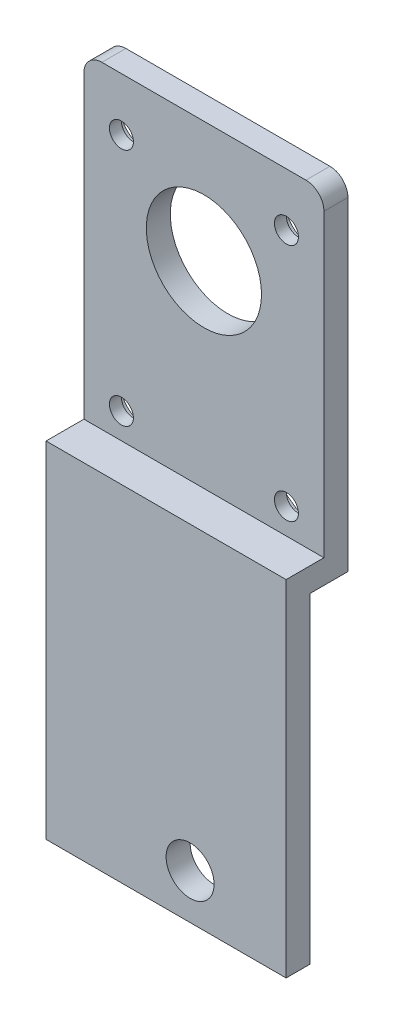
SolidWorks part; units mm, degrees
ref_plane "Front Plane" through (0, 0, 0) normal (0, 0, 1) x (1, 0, 0)
ref_plane "Top Plane" through (0, 0, 0) normal (0, 1, 0) x (1, 0, 0)
ref_plane "Right Plane" through (0, 0, 0) normal (1, 0, 0) x (0, 0, -1)
sketch "Sketch1" plane through (0, 0, 0) normal (0, 0, 1) x (1, 0, 0)
  line L0 (13.75, -19.7) -> (9.6769, -16.8) construction
  line L8 (20, -29) -> (-20, -29)
  line L9 (20, -29) -> (20, 26)
  line L11 (17, 29) -> (-17, 29)
  line L14 (-20, -29) -> (-20, 26)
  line L15 (20, -29) -> (-20, 29) construction
  line L16 (20, 29) -> (-20, -29) construction
  line L17 (11.314, -23.1214) -> (7.2409, -20.2214)
  line L18 (16.186, -16.2786) -> (12.1129, -13.3786)
  line L19 (0, -29) -> (0, 29) construction
  circle A18 centre (-13.75, 20.15) radius 4.2
  circle A19 centre (13.75, 20.15) radius 4.2
  circle A20 centre (-13.75, -19.7) radius 4.2
  arc A21 (11.314, -23.1214) -> (16.186, -16.2786) centre (13.75, -19.7) ccw
  arc A22 (12.1129, -13.3786) -> (7.2409, -20.2214) centre (9.6769, -16.8) ccw
  circle A23 centre (0, 8.8) radius 9.6
  circle A24 centre (-5.725, -6.1) radius 4.2
  circle A25 centre (5.725, -6.1) radius 4.2
  arc A26 (20, 26) -> (17, 29) centre (17, 26) ccw
  arc A27 (-20, 26) -> (-17, 29) centre (-17, 26) cw
  point P0 (0, 0)
  point P9 (0, 0)
  point P10 (19.6497, -28.492)
  point P12 (0, 0)
  point P13 (0, 0)
  point P14 (6.2555, -14.364)
  point P15 (0, 0)
  point P19 (0, 0)
  point P21 (0, 0)
  point P22 (0, 0)
  point P31 (11.7135, -18.25)
  point P37 (5.725, -10.3)
  point P38 (0, 0)
  point P39 (0, 0)
  point P43 (20, 29)
  point P46 (-20, 29)
  point P47 (1.9002, -20.2214)
  point P48 (-25.7648, -19.7)
  point P49 (-5.725, -14.8966)
  point P50 (7.0698, -20.2214)
  point P51 (-36.8241, -19.7)
  point P52 (11.0425, -18.4247)
  point P54 (0, 0)
  point P55 (0, 0)
  dimension "D1" = 58
  dimension "D2" = 40
  dimension "D3" = 3
  dimension "D4" = 8.4
  dimension "D5" = 8.4
  dimension "D6" = 19.2
  dimension "D7" = 9.3
  dimension "D8" = 27.5
  dimension "D9" = 12.2
  dimension "D10" = 5
  dimension "D11" = 39.85
  dimension "D12" = 20.2
  dimension "D13" = 11.45
  dimension "D14" = 22.9
extrude "Boss-Extrude1" add sketch "Sketch1" along normal blind 2
sketch "Sketch2" plane through (0, -29, 0) normal (0, -1, 0) x (1, 0, 0)
  line L1 (-20, 2) -> (20, 2)
  line L2 (-20, 2) -> (-20, 0)
  line L3 (-20, 0) -> (20, 0)
  line L4 (20, 2) -> (20, 0)
  point P6 (20, 2)
  point P8 (-20, 0)
extrude "Cut-Extrude1" cut sketch "Sketch2" against normal blind 1
sketch "Sketch4" plane through (0, 0, 2) normal (0, 0, 1) x (1, 0, 0)
  line L0 (20, -28) -> (20, 26) construction
  line L1 (-17, 29) -> (17, 29)
  line L2 (-20, 26) -> (-20, -28)
  line L3 (-20, -28) -> (20, -28)
  line L4 (20, 26) -> (20, -28)
  line L5 (-20, -28) -> (-20, 26) construction
  line L6 (20, -28) -> (-20, -28) construction
  line L7 (17, 29) -> (-17, 29) construction
  circle A2 centre (-13.75, -19.7) radius 2
  circle A3 centre (-13.75, 20.15) radius 2
  circle A4 centre (13.75, 20.15) radius 2
  arc A8 (17, 29) -> (20, 26) centre (17, 26) cw
  arc A9 (-17, 29) -> (-20, 26) centre (-17, 26) ccw
  circle A10 centre (13.75, -19.7) radius 2
  circle A11 centre (0, 8.8) radius 9.6
  circle A12 centre (0, 8.8) radius 9.6 construction
  dimension "D1" = 4
  dimension "D2" = 3
extrude "Boss-Extrude3" add sketch "Sketch4" along normal blind 2
sketch "Sketch5" plane through (0, 0, 4) normal (0, 0, 1) x (1, 0, 0)
  line L0 (-20, 26) -> (-20, -28) construction
  line L1 (-20, -24) -> (20, -24)
  line L2 (-20, -24) -> (-20, -28)
  line L3 (-20, -28) -> (20, -28)
  line L4 (20, -24) -> (20, -28)
  line L5 (20, -28) -> (20, 26) construction
  dimension "D1" = 4
extrude "Boss-Extrude4" add sketch "Sketch5" along normal blind 2.3
sketch "Sketch7" plane through (0, 0, 6.3) normal (0, 0, 1) x (1, 0, 0)
  line L0 (20, -24) -> (20, 26) construction
  line L1 (-20, -24) -> (20, -24)
  line L2 (-20, -24) -> (-20, -81.5)
  line L3 (-20, -81.5) -> (20, -81.5)
  line L4 (20, -24) -> (20, -81.5)
  circle A0 centre (4, -74) radius 4
  dimension "D2" = 8
  dimension "D1" = 57.5
  dimension "D3" = 50
  dimension "D4" = 16
extrude "Boss-Extrude6" add sketch "Sketch7" along normal blind 4
